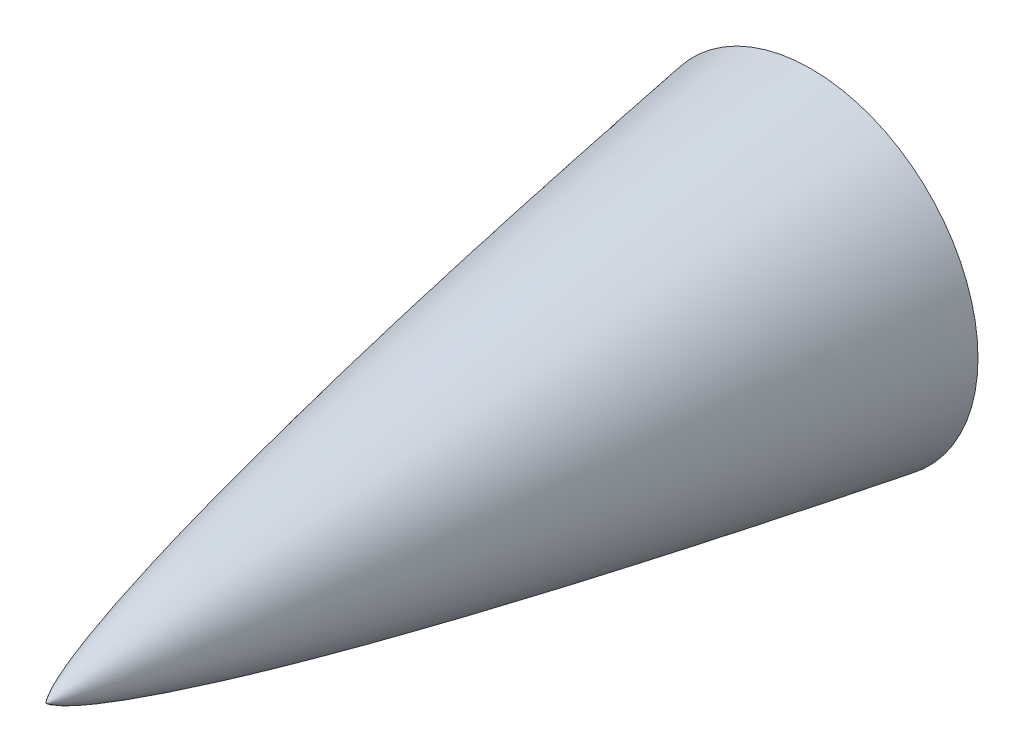
SolidWorks part; units mm, degrees
material "6061 Alloy"
ref_plane "Front Plane" through (0, 0, 0) normal (0, 0, 1) x (1, 0, 0)
ref_plane "Top Plane" through (0, 0, 0) normal (0, 1, 0) x (1, 0, 0)
ref_plane "Right Plane" through (0, 0, 0) normal (1, 0, 0) x (0, 0, -1)
sketch "Sketch1" plane through (0, 0, 0) normal (1, 0, 0) x (0, 0, -1)
  line L0 (76.2, 15.9695) -> (76.2, 0)
  line L1 (76.2, 0) -> (0, 0)
  line L2 (65.786, 0) -> (65.786, 14.3515)
  spline S0 degree 4 poles (0, 0) (0.0027, 0.0076) (0.0099, 0.0219) (0.0286, 0.0451) (0.0582, 0.0762) (0.0981, 0.112) (0.1545, 0.1573) (0.237, 0.2168) (0.3691, 0.3025) (0.5867, 0.4286) (0.961, 0.6211) (1.6164, 0.9181) (2.772, 1.3762) (4.7086, 2.0452) (7.8503, 2.9954) (12.073, 4.1191) (17.1358, 5.335) (22.7175, 6.5689) (28.3162, 7.7294) (33.9244, 8.8318) (39.545, 9.8878) (45.167, 10.9033) (50.1011, 11.7633) (54.3184, 12.4794) (57.8587, 13.0683) (60.6493, 13.5264) (63.5272, 13.9914) (66.2527, 14.4272) (69.2402, 14.897) (71.7862, 15.2942) (75.3797, 15.8457) (77.8389, 16.2186) (81.3551, 16.7468) (82.6674, 16.9389) (83.8861, 17.1198) knots 0 0 0 0 0 0.000375 0.000749 0.001378 0.002004 0.002871 0.004125 0.006122 0.009343 0.014599 0.023751 0.039674 0.067305 0.11015 0.176817 0.243484 0.31015 0.376817 0.443483 0.51015 0.576816 0.643483 0.676816 0.710149 0.743483 0.776816 0.810149 0.843482 0.876816 0.910149 0.955074 1 1 1 1 1 construction
  spline S1 degree 4 poles (0, 0) (0.0027, 0.0076) (0.0099, 0.0219) (0.0286, 0.0451) (0.0582, 0.0762) (0.0981, 0.112) (0.1545, 0.1573) (0.237, 0.2168) (0.3691, 0.3025) (0.5867, 0.4286) (0.961, 0.6211) (1.6164, 0.9181) (2.772, 1.3762) (4.7086, 2.0452) (7.8503, 2.9954) (12.073, 4.1191) (17.1358, 5.335) (22.7175, 6.5689) (28.3162, 7.7294) (33.9244, 8.8318) (39.545, 9.8878) (45.167, 10.9033) (50.1011, 11.7633) (54.3184, 12.4794) (57.8587, 13.0683) (60.6493, 13.5264) (63.5272, 13.9914) (66.2527, 14.4272) (69.2402, 14.897) (71.7862, 15.2942) (74.2657, 15.6747) (75.557, 15.8718) (76.2, 15.9695) knots 0 0 0 0 0 0.000375 0.000749 0.001378 0.002004 0.002871 0.004125 0.006122 0.009343 0.014599 0.023751 0.039674 0.067305 0.11015 0.176817 0.243484 0.31015 0.376817 0.443483 0.51015 0.576816 0.643483 0.676816 0.710149 0.743483 0.776816 0.810149 0.843482 0.876816 0.910149 0.910149 0.910149 0.910149 0.910149
  dimension "D1" = 65.786
revolve "Revolve1" add sketch "Sketch1" angle 360 about L1
hole_wizard "1/4-20 Tapped Hole1" positions "Sketch3" profile "Sketch2" tap size "1/4-20" standard "ANSI Inch"
sketch "Sketch3" plane through (0, 0, -65.786) normal (0, 0, -1) x (-1, 0, 0)
  point P0 (0, 0)
sketch "Sketch2" plane through (0, 0, -65.786) normal (1, 0, 0) x (0, 1, 0)
  line L0 (0, 0) -> (0, 21.3458)
  line L1 (0, 21.3458) -> (2.5527, 19.812)
  line L2 (2.5527, 19.812) -> (2.5527, 0)
  line L5 (2.5527, 0) -> (0, 0)
  line L10 (0, 21.3458) -> (-2.5527, 19.812) construction
  line L11 (0, -6.35) -> (0, 107.95) construction
  dimension "Tap Drill Dia." = 5.1054
  dimension "Tap Drill Depth" = 19.812
  dimension "Drill Angle" = 118
cosmetic thread "Hole Thread3"
